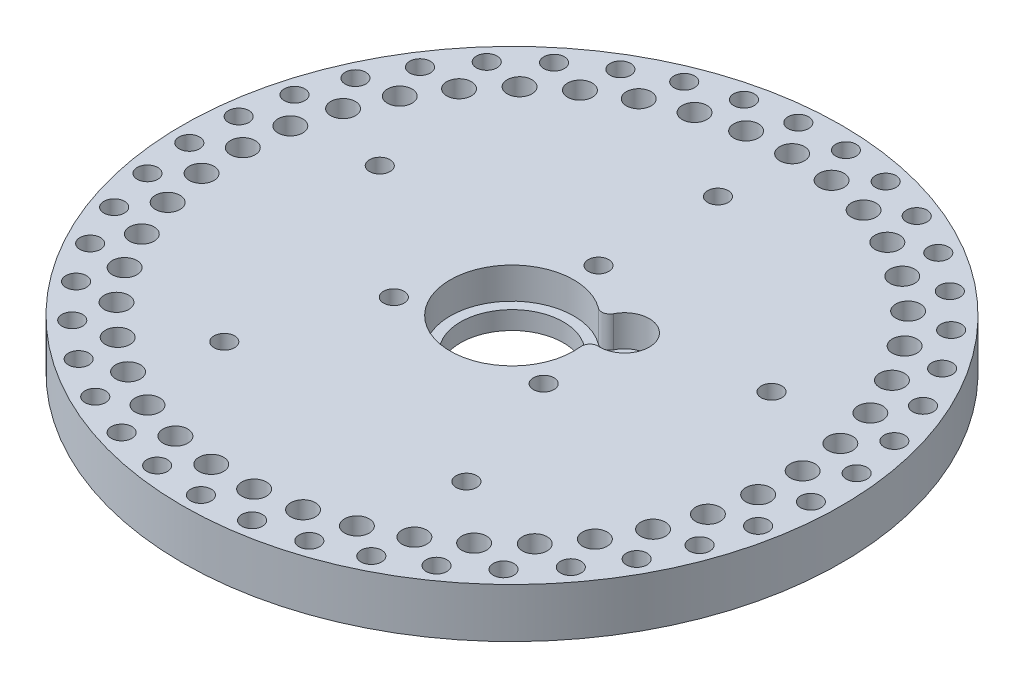
SolidWorks part; units mm, degrees
material "6061 Alloy"
ref_plane "Front Plane" through (0, 0, 0) normal (0, 0, 1) x (1, 0, 0)
ref_plane "Top Plane" through (0, 0, 0) normal (0, 1, 0) x (1, 0, 0)
ref_plane "Right Plane" through (0, 0, 0) normal (1, 0, 0) x (0, 0, -1)
sketch "Sketch1" plane through (0, 0, 0) normal (0, 1, 0) x (1, 0, 0)
  circle A0 centre (0, 0) radius 40
  dimension "D1" = 80
extrude "podstawa" add sketch "Sketch1" along normal blind 6
sketch "Sketch2" plane through (0, 6, 0) normal (0, 1, 0) x (1, 0, 0)
  circle A0 centre (0, 0) radius 7.5
  dimension "D1" = 15
extrude "przelot sprzegla" cut sketch "Sketch2" against normal up to next and the other way through all
hole_wizard "walki cykloidy" positions "Sketch3" profile "Sketch5" hole size "Ø3.0" standard "DIN" end condition up to next
sketch "Sketch3" plane through (0, 6, 0) normal (0, 1, 0) x (1, 0, 0)
  line L0 (0, 34) -> (0, 40) construction
  circle A0 centre (0, 0) radius 40 construction
  point P0 (0, 34)
  point P15 (5.1901, 33.6015)
  point P16 (10.2585, 32.4155)
  point P17 (15.0865, 30.4696)
  point P18 (19.5608, 27.8096)
  point P19 (23.5767, 24.4977)
  point P20 (27.04, 20.6117)
  point P21 (29.8694, 16.2425)
  point P22 (31.9988, 11.4926)
  point P23 (33.3781, 6.4733)
  point P24 (33.9751, 1.3023)
  point P25 (33.7757, -3.8992)
  point P26 (32.7846, -9.0094)
  point P27 (31.0251, -13.9083)
  point P28 (28.5384, -18.4813)
  point P29 (25.3828, -22.6211)
  point P30 (21.6322, -26.2306)
  point P31 (17.3746, -29.2254)
  point P32 (12.7098, -31.5351)
  point P33 (7.747, -33.1056)
  point P34 (2.6027, -33.9002)
  point P35 (-2.6027, -33.9002)
  point P36 (-7.747, -33.1056)
  point P37 (-12.7098, -31.5351)
  point P38 (-17.3746, -29.2254)
  point P39 (-21.6322, -26.2306)
  point P40 (-25.3828, -22.6211)
  point P41 (-28.5384, -18.4813)
  point P42 (-31.0251, -13.9083)
  point P43 (-32.7846, -9.0094)
  point P44 (-33.7757, -3.8992)
  point P45 (-33.9751, 1.3023)
  point P46 (-33.3781, 6.4733)
  point P47 (-31.9988, 11.4926)
  point P48 (-29.8694, 16.2425)
  point P49 (-27.04, 20.6117)
  point P63 (-23.5767, 24.4977)
  point P64 (-19.5608, 27.8096)
  point P65 (-15.0865, 30.4696)
  point P66 (-10.2585, 32.4155)
  point P67 (-5.1901, 33.6015)
  dimension "D1" = 6
  dimension "D2" = 41
sketch "Sketch5" plane through (0, 6, -34) normal (1, 0, 0) x (0, 0, 1)
  line L0 (0, 0) -> (0, 6)
  line L1 (0, 6) -> (1.5, 6)
  line L2 (1.5, 6) -> (1.5, 0)
  line L5 (1.5, 0) -> (0, 0)
  line L11 (0, -6.35) -> (0, 107.95) construction
  dimension "Thru Hole Dia." = 3
  dimension "Thru Hole Depth" = 6
hole_wizard "Tap Drill for M3 Tap1" positions "Sketch7" profile "Sketch8" hole size "M3" standard "DIN" end condition up to next
sketch "Sketch7" plane through (0, 6, 0) normal (0, 1, 0) x (1, 0, 0)
  line L0 (0, 0) -> (0, 34)
  line L2 (0, 0) -> (5.1901, 33.6015)
  line L4 (5.1901, 33.6015) -> (0, 34)
  line L6 (3.2233, 41.9837) -> (0, 0)
  circle A0 centre (0, 0) radius 35.5
  circle A1 centre (0, 0) radius 40
  circle A3 centre (0, 0) radius 37.75 construction
  point P33 (2.8897, 37.6392)
  point P40 (8.6015, 36.757)
  point P41 (14.1116, 35.0132)
  point P42 (19.291, 32.4488)
  point P43 (24.0182, 29.1237)
  point P44 (28.1824, 25.116)
  point P45 (31.686, 20.5197)
  point P46 (34.447, 15.4423)
  point P47 (36.4006, 10.0031)
  point P48 (37.5009, 4.3293)
  point P49 (37.7223, -1.4459)
  point P50 (37.0595, -7.1873)
  point P51 (35.528, -12.7601)
  point P52 (33.1638, -18.0339)
  point P53 (30.0223, -22.885)
  point P54 (26.1771, -27.1997)
  point P55 (21.7183, -30.8768)
  point P56 (16.7504, -33.8302)
  point P57 (11.39, -35.9907)
  point P58 (5.7625, -37.3076)
  point P59 (0, -37.75)
  point P60 (-5.7625, -37.3076)
  point P61 (-11.39, -35.9907)
  point P62 (-16.7504, -33.8302)
  point P63 (-21.7183, -30.8768)
  point P64 (-26.1771, -27.1997)
  point P65 (-30.0223, -22.885)
  point P66 (-33.1638, -18.0339)
  point P67 (-35.528, -12.7601)
  point P68 (-37.0595, -7.1873)
  point P69 (-37.7223, -1.4459)
  point P70 (-37.5009, 4.3293)
  point P71 (-36.4006, 10.0031)
  point P72 (-34.447, 15.4423)
  point P73 (-31.686, 20.5197)
  point P74 (-28.1824, 25.116)
  point P75 (-24.0182, 29.1237)
  point P76 (-19.291, 32.4488)
  point P77 (-14.1116, 35.0132)
  point P78 (-8.6015, 36.757)
  point P79 (-2.8897, 37.6392)
  dimension "D1" = 80
  dimension "D2" = 71
  dimension "D3" = 75.5
  dimension "D4" = 41
sketch "Sketch8" plane through (-2.8897, 6, -37.6392) normal (1, 0, 0) x (0, 0, 1)
  line L0 (0, 0) -> (0, 6)
  line L1 (0, 6) -> (1.25, 6)
  line L2 (1.25, 6) -> (1.25, 0)
  line L5 (1.25, 0) -> (0, 0)
  line L11 (0, -6.35) -> (0, 107.95) construction
  dimension "Thru Hole Dia." = 2.5
  dimension "Thru Hole Depth" = 6
sketch "Sketch9" plane through (0, 0, 0) normal (0, 1, 0) x (1, 0, 0)
  circle A1 centre (0, 0) radius 7.5 construction
  circle A2 centre (0, 0) radius 6.25
  circle A3 centre (0, 0) radius 6.25
  circle A4 centre (0, 0) radius 7.5
  dimension "D1" = 1.25
extrude "prog lozyska" add sketch "Sketch9" along normal blind 2.2
hole_wizard "Tap Drill for M3 Tap2" positions "Sketch10" profile "Sketch11" hole size "M3" standard "DIN" end condition up to next
sketch "Sketch10" plane through (0, 6, 0) normal (0, 1, 0) x (1, 0, 0)
  line L0 (0, 10.5) -> (0, 0)
  circle A0 centre (0, 10.5) radius 2.75
  circle A1 centre (0, 10.5) radius 3
  circle A3 centre (0, 0) radius 7.5 construction
  point P0 (0, 10.5)
  point P16 (9.0933, -5.25)
  point P17 (-9.0933, -5.25)
  dimension "D1" = 5.5
  dimension "D3" = 6
  dimension "D2" = 3
sketch "Sketch11" plane through (0, 6, -10.5) normal (1, 0, 0) x (0, 0, 1)
  line L0 (0, 0) -> (0, 6)
  line L1 (0, 6) -> (1.25, 6)
  line L2 (1.25, 6) -> (1.25, 0)
  line L5 (1.25, 0) -> (0, 0)
  line L11 (0, -6.35) -> (0, 107.95) construction
  dimension "Thru Hole Dia." = 2.5
  dimension "Thru Hole Depth" = 6
sketch "Sketch12" plane through (0, 6, 0) normal (0, 1, 0) x (1, 0, 0)
  line L0 (0, 10.5) -> (9.0933, -5.25) construction
  line L1 (0, 0) -> (19.6616, 11.3517) construction
  line L2 (6.4952, 3.75) -> (6.0622, 3.5) construction
  circle A1 centre (8.6603, 5) radius 3
  circle A2 centre (0, 0) radius 7.5 construction
  dimension "D1" = 6
  dimension "D2" = 0.5
extrude "Cut-Extrude1" cut sketch "Sketch12" against normal up to surface (3.8 mm away) up to face at (0, 2.2, 7.5)
fillet "Fillet1" radius 1 2 edges at (7.0909, 4.1, -2.4432) (5.6613, 4.1, -4.9193)
hole_wizard "Tap Drill for M3 Tap3" positions "Sketch14" profile "Sketch15" hole size "M3" standard "DIN"
sketch "Sketch14" plane through (0, 6, 0) normal (0, 1, 0) x (1, 0, 0)
  point P0 (0, 25)
  point P9 (23.7764, 7.7254)
  point P10 (14.6946, -20.2254)
  point P11 (-14.6946, -20.2254)
  point P12 (-23.7764, 7.7254)
  dimension "D1" = 25
  dimension "D2" = 5
sketch "Sketch15" plane through (0, 6, -25) normal (1, 0, 0) x (0, 0, 1)
  line L0 (0, 0) -> (0, 6.7511)
  line L1 (0, 6.7511) -> (1.25, 6)
  line L2 (1.25, 6) -> (1.25, 0)
  line L5 (1.25, 0) -> (0, 0)
  line L10 (0, 6.7511) -> (-1.25, 6) construction
  line L11 (0, -6.35) -> (0, 107.95) construction
  dimension "Hole Dia." = 2.5
  dimension "Hole Depth" = 6
  dimension "Drill Angle" = 118
equation "\"D3@Sketch7\"=(\"D2@Sketch7\"+\"D1@Sketch7\")/2"
